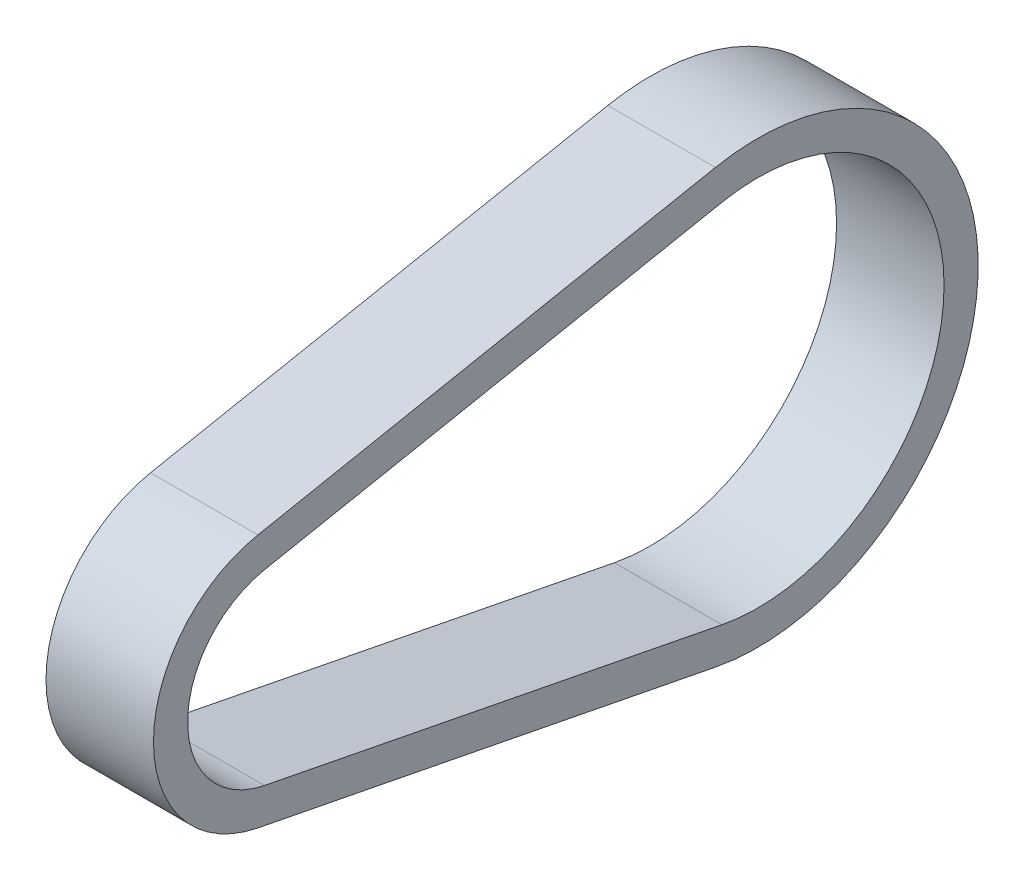
SolidWorks part; units mm, degrees
ref_plane "Front Plane" through (0, 0, 0) normal (0, 0, 1) x (1, 0, 0)
ref_plane "Top Plane" through (0, 0, 0) normal (0, 1, 0) x (1, 0, 0)
ref_plane "Right Plane" through (0, 0, 0) normal (1, 0, 0) x (0, 0, -1)
other "Bounding Box"
ref_plane "Default Plane" through (-8.9266, -12.7485, 0) normal (-0.1736, 0.9848, 0) x (0.9848, 0.1736, 0)
sketch "Sketch1" plane through (0, 0, 0) normal (1, 0, 0) x (0, 0, -1)
  line L0 (0, 0) -> (66.2737, 0) construction
  line L1 (-2.5507, 13.037) -> (61.2795, 25.5256)
  line L2 (-2.5507, -13.037) -> (61.2795, -25.5256)
  line L3 (-3.4652, 17.7109) -> (60.365, 30.1995)
  line L4 (-3.4652, -17.7109) -> (60.365, -30.1995)
  line L5 (-13.2842, 0) -> (-18.0467, 0) construction
  line L6 (92.2833, 0) -> (97.0458, 0) construction
  arc A0 (-2.5507, 13.037) -> (-2.5507, -13.037) centre (0, 0) ccw
  arc A1 (61.2795, -25.5256) -> (61.2795, 25.5256) centre (66.2737, 0) ccw
  arc A2 (-3.4652, 17.7109) -> (-3.4652, -17.7109) centre (0, 0) ccw
  arc A3 (60.365, -30.1995) -> (60.365, 30.1995) centre (66.2737, 0) ccw
  dimension "D2" = 4.7625
  dimension "D4" = 26.5684
  dimension "D5" = 52.0192
  dimension "D1" = 66.2737
extrude "Boss-Extrude1" add sketch "Sketch1" along normal mid plane 15
